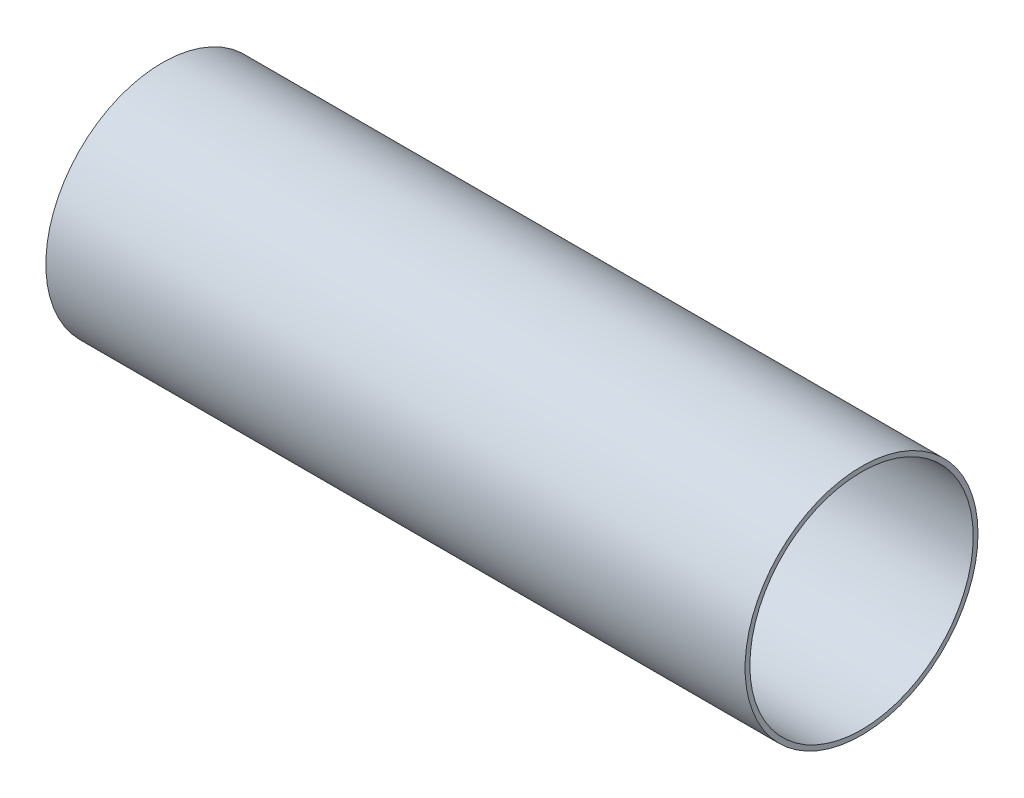
SolidWorks part; units mm, degrees
ref_plane "Front Plane" through (0, 0, 0) normal (1, 0, 0) x (0, 1, 0)
ref_plane "Top Plane" through (0, 0, 0) normal (0, 0, 1) x (0, 1, 0)
ref_plane "Right Plane" through (0, 0, 0) normal (0, 1, 0) x (-1, 0, 0)
sketch "Sketch1" plane through (0, 0, 0) normal (1, 0, 0) x (0, 1, 0)
  circle A0 centre (0, 0) radius 36.5125
  circle A1 centre (0, 0) radius 38.0746
  dimension "D1" = 76.1492
  dimension "D2" = 73.025
extrude "Boss-Extrude1" add sketch "Sketch1" along normal blind 228.6
